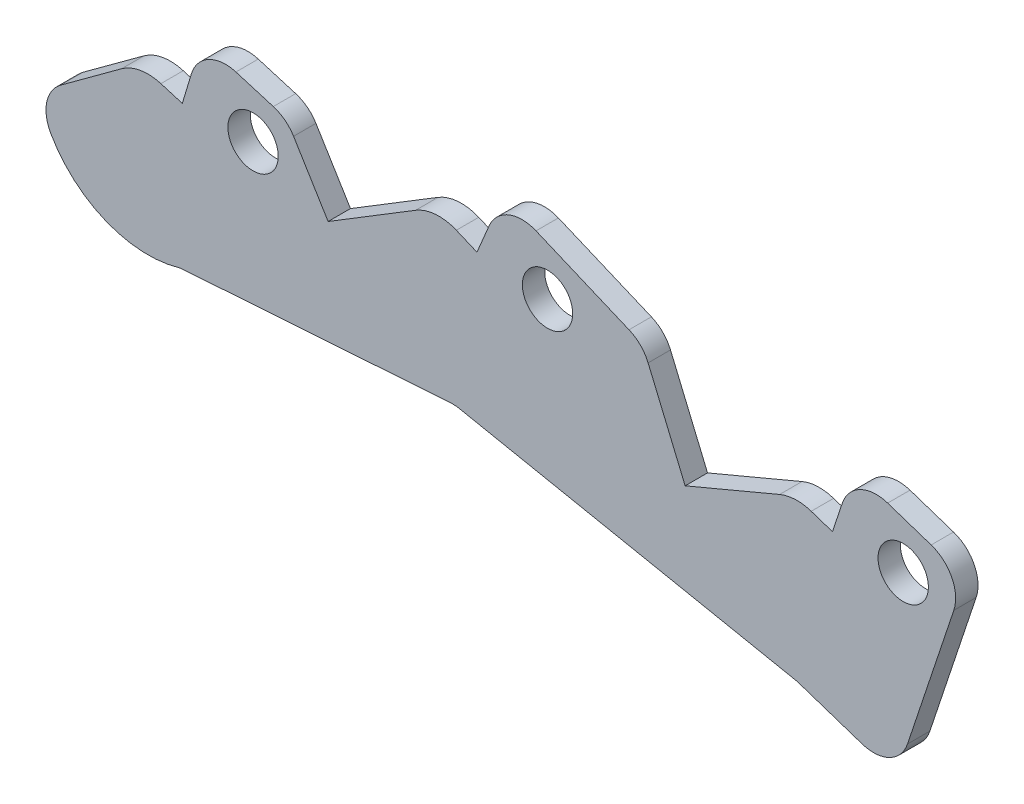
SolidWorks part; units mm, degrees
ref_plane "Front Plane" through (0, 0, 0) normal (0, 0, 1) x (1, 0, 0)
ref_plane "Top Plane" through (0, 0, 0) normal (0, 1, 0) x (1, 0, 0)
ref_plane "Right Plane" through (0, 0, 0) normal (1, 0, 0) x (0, 0, -1)
sketch "Sketch1" plane through (0, 0, 0) normal (0, 0, 1) x (1, 0, 0)
  line L0 (-51.2912, 76.2) -> (64262.6532, 76.2) construction
  line L5 (7.4715, 147.6375) -> (64321.4159, 147.6375) construction
  line L6 (118.3446, 158.75) -> (64432.2889, 158.75) construction
  line L7 (275.7842, 163.5125) -> (64589.7286, 163.5125) construction
  line L8 (55.5625, 439.4786) -> (55.5625, -63874.4658) construction
  line L9 (111.125, 452.7834) -> (111.125, -63861.161) construction
  line L10 (119.0625, 453.8921) -> (119.0625, -63860.0523) construction
  line L11 (99.4961, 73.025) -> (64413.4405, 73.025) construction
  line L12 (93.9525, 3.175) -> (64407.8969, 3.175) construction
  line L13 (33.9504, 0) -> (64347.8947, 0) construction
  line L14 (-39.0951, -3.175) -> (64274.8492, -3.175) construction
  line L15 (-110.0539, -73.025) -> (64203.8905, -73.025) construction
  line L16 (198.1731, 65.0875) -> (64512.1175, 65.0875) construction
  line L17 (201.4993, 77.7875) -> (64515.4437, 77.7875) construction
  line L18 (276.893, 155.575) -> (64590.8373, 155.575) construction
  line L19 (351.1779, 168.275) -> (64665.1223, 168.275) construction
  line L20 (107.95, 410.6516) -> (107.95, -63903.2928) construction
  line L21 (95.25, 453.8921) -> (95.25, -63860.0523) construction
  line L22 (87.3125, 480.5016) -> (87.3125, -63833.4428) construction
  line L23 (34.925, 470.523) -> (34.925, -63843.4213) construction
  line L24 (0, 558.1122) -> (0, -63755.8322) construction
  line L25 (127, 731.8887) -> (127, -63582.0557) construction
  line L26 (133.35, 785.5707) -> (133.35, -63528.3737) construction
  line L27 (146.05, 782.952) -> (146.05, -63530.9923) construction
  line L28 (147.6375, 792.1173) -> (147.6375, -63521.8271) construction
  line L29 (152.4, 819.6129) -> (152.4, -63494.3315) construction
  line L30 (161.925, 852.3458) -> (161.925, -63461.5986) construction
  line L31 (206.375, 822.2315) -> (206.375, -63491.7129) construction
  line L32 (-303.6442, 138.1125) -> (49696.3558, 138.1125) construction
  line L33 (-178.9515, 120.65) -> (49821.0485, 120.65) construction
  point P60 (111.125, -3.175)
  point P61 (119.0625, 0)
  point P62 (133.35, 3.175)
  point P63 (147.6375, 3.175)
  point P64 (107.95, 77.7875)
  point P65 (133.35, 73.025)
  point P66 (152.4, 65.0875)
  point P67 (87.3125, 76.2)
  point P68 (34.925, 147.6375)
  point P69 (55.5625, 163.5125)
  point P70 (111.125, 155.575)
  point P71 (95.25, 163.5125)
  point P72 (127, 138.1125)
  point P73 (146.05, 168.275)
  point P74 (161.925, 158.75)
  point P77 (206.375, 120.65)
  dimension "D1" = 69.85
  dimension "D2" = 73.025
  dimension "D3" = 76.2
  dimension "D4" = 138.1125
  dimension "D5" = 146.05
  dimension "D6" = 150.8125
  dimension "D7" = 149.225
  dimension "D8" = 211.1375
  dimension "D9" = 220.6625
  dimension "D10" = 228.6
  dimension "D11" = 231.775
  dimension "D12" = 236.5375
  dimension "D13" = 241.3
  dimension "D14" = 34.925
  dimension "D15" = 55.5625
  dimension "D16" = 87.3125
  dimension "D17" = 95.25
  dimension "D18" = 107.95
  dimension "D19" = 111.125
  dimension "D20" = 119.0625
  dimension "D21" = 127
  dimension "D22" = 133.35
  dimension "D23" = 146.05
  dimension "D24" = 147.6375
  dimension "D25" = 152.4
  dimension "D26" = 161.925
  dimension "D27" = 206.375
  dimension "D28" = 193.675
sketch "Sketch2" plane through (0, 0, 0) normal (0, 0, 1) x (1, 0, 0)
  line L0 (111.125, -3.175) -> (87.3125, 76.2)
  line L1 (119.0625, 0) -> (107.95, 77.7875)
  line L2 (133.35, 3.175) -> (133.35, 73.025)
  line L3 (147.6375, 3.175) -> (152.4, 65.0875)
  line L4 (152.4, 65.0875) -> (206.375, 120.65)
  line L5 (152.4, 65.0875) -> (127, 138.1125)
  line L6 (133.35, 73.025) -> (161.925, 158.75)
  line L7 (-199881.6554, 158.75) -> (264432.2889, 158.75) construction
  line L8 (133.35, 73.025) -> (95.25, 163.5125)
  line L9 (107.95, 77.7875) -> (146.05, 168.275)
  line L10 (107.95, 77.7875) -> (55.5625, 163.5125)
  line L11 (87.3125, 76.2) -> (111.125, 155.575)
  line L12 (87.3125, 76.2) -> (34.925, 147.6375)
  point P16 (0, 0)
sketch "Sketch4" plane through (0, 0, 0) normal (0, 0, 1) x (1, 0, 0)
  line L0 (87.3125, 76.2) -> (107.95, 77.7875) construction
  line L1 (107.95, 77.7875) -> (133.35, 73.025) construction
  line L2 (133.35, 73.025) -> (152.4, 65.0875) construction
  line L3 (94.8094, 73.5923) -> (100.9401, 74.0639)
  line L4 (114.5151, 73.3262) -> (125.6146, 71.2451)
  line L5 (138.8441, 67.2962) -> (146.05, 64.2937)
  line L6 (111.125, -3.175) -> (87.3125, 76.2) construction
  line L7 (107.1642, 77.6752) -> (108.2868, 69.8175) construction
  line L8 (141.2864, 73.1578) -> (146.9059, 70.8163)
  line L9 (87.069, 79.3656) -> (108.1238, 80.9852) construction
  line L10 (87.556, 73.0344) -> (107.7762, 74.5898) construction
  line L11 (134.2631, 76.0841) -> (153.6212, 68.0183) construction
  line L12 (132.4369, 69.9659) -> (151.1788, 62.1567) construction
  line L13 (146.05, 200782.952) -> (146.05, -263530.9923) construction
  line L14 (108.1238, 80.9852) -> (134.2631, 76.0841) construction
  line L15 (107.7762, 74.5898) -> (132.4369, 69.9659) construction
  line L16 (108.7358, 77.8998) -> (109.8583, 70.042) construction
  line L17 (107.3887, 76.1037) -> (108.9603, 76.3282)
  line L18 (94.3224, 79.9236) -> (100.4531, 80.3952)
  line L19 (115.6854, 79.5674) -> (126.7849, 77.4863)
  line L20 (132.5563, 73.025) -> (132.5563, 65.0875) construction
  line L21 (134.1438, 73.025) -> (134.1438, 65.0875) construction
  line L22 (132.5563, 71.4773) -> (134.1438, 71.4773)
  line L23 (151.4899, 63.6052) -> (151.0029, 57.2739)
  line L24 (153.0727, 63.4835) -> (152.5857, 57.1522)
  line L25 (151.4899, 63.6052) -> (153.0727, 63.4835)
  line L26 (152.4, 65.0875) -> (206.375, 120.65) construction
  line L27 (152.4, 65.0875) -> (127, 138.1125) construction
  line L28 (133.35, 73.025) -> (161.925, 158.75) construction
  line L29 (133.35, 73.025) -> (95.25, 163.5125) construction
  line L30 (87.3125, 76.2) -> (89.5933, 68.5973)
  line L31 (107.95, 77.7875) -> (109.0725, 69.9298)
  line L32 (119.0625, 0) -> (107.95, 77.7875) construction
  line L33 (133.35, 73.025) -> (133.35, 65.0875)
  line L34 (152.4, 65.0875) -> (151.7912, 57.1734)
  line L35 (147.6375, 3.175) -> (152.4, 65.0875) construction
  line L36 (87.0084, 74.4514) -> (88.8216, 68.4073)
  line L37 (107.3887, 76.1037) -> (108.2811, 69.8569)
  line L38 (132.5563, 71.4773) -> (132.5563, 65.1273)
  line L39 (107.95, 77.7875) -> (146.05, 168.275) construction
  line L40 (88.5289, 74.9075) -> (90.3422, 68.8634)
  line L41 (108.9603, 76.3282) -> (109.8527, 70.0814)
  line L42 (134.1438, 71.4773) -> (134.1438, 65.1273)
  line L43 (107.95, 77.7875) -> (55.5625, 163.5125) construction
  line L44 (88.0728, 76.4281) -> (90.3536, 68.8253) construction
  line L45 (86.5522, 75.9719) -> (88.833, 68.3692) construction
  line L46 (87.0084, 74.4514) -> (88.5289, 74.9075)
  line L47 (87.3125, 76.2) -> (111.125, 155.575) construction
  line L48 (87.3125, 76.2) -> (34.925, 147.6375) construction
  line L49 (83.5573, 81.3207) -> (85.4349, 78.7603)
  line L50 (88.2248, 79.2411) -> (89.1372, 82.2822)
  line L51 (106.2944, 80.4967) -> (104.6388, 83.2058)
  line L52 (109.1821, 80.7137) -> (110.4142, 83.6399)
  line L53 (132.1179, 75.9512) -> (130.8858, 78.8774)
  line L54 (134.354, 76.0371) -> (135.358, 79.0491)
  line L55 (151.3569, 68.0863) -> (150.3139, 71.0851)
  line L56 (154.6123, 67.3649) -> (156.8246, 69.6422)
  line L57 (82.2772, 80.3819) -> (84.1548, 77.8215)
  line L58 (89.7454, 78.7849) -> (90.6577, 81.826)
  line L59 (110.6452, 80.0977) -> (111.8773, 83.0238)
  line L60 (135.8601, 75.5351) -> (136.8641, 78.5471)
  line L61 (155.751, 66.2587) -> (157.9633, 68.5361)
  line L62 (149.8576, 67.5648) -> (148.8145, 70.5635)
  line L63 (130.6548, 75.3352) -> (129.4227, 78.2613)
  line L64 (104.9398, 79.6689) -> (103.2842, 82.378)
  line L65 (83.5573, 81.3207) -> (82.2772, 80.3819)
  line L66 (156.8246, 69.6422) -> (157.9633, 68.5361)
  line L67 (84.1548, 77.8215) -> (85.4349, 78.7603)
  line L68 (88.2248, 79.2411) -> (89.7454, 78.7849)
  line L69 (154.6123, 67.3649) -> (155.751, 66.2587)
  line L70 (149.8576, 67.5648) -> (151.3569, 68.0863)
  line L71 (148.8145, 70.5635) -> (150.3139, 71.0851)
  line L72 (129.4227, 78.2613) -> (130.8858, 78.8774)
  line L73 (130.6548, 75.3352) -> (132.1179, 75.9512)
  line L74 (135.358, 79.0491) -> (136.8641, 78.5471)
  line L75 (134.354, 76.0371) -> (135.8601, 75.5351)
  line L76 (89.1372, 82.2822) -> (90.6577, 81.826)
  line L77 (103.2842, 82.378) -> (104.6388, 83.2058)
  line L78 (104.9398, 79.6689) -> (106.2944, 80.4967)
  line L79 (110.4142, 83.6399) -> (111.8773, 83.0238)
  line L80 (109.1821, 80.7137) -> (110.6452, 80.0977)
  circle A0 centre (87.3125, 76.2) radius 7.9375
  circle A1 centre (107.95, 77.7875) radius 7.9375
  circle A2 centre (133.35, 73.025) radius 7.9375
  circle A3 centre (152.4, 65.0875) radius 7.9375
  circle A16 centre (152.4, 65.0875) radius 4.7625 construction
  circle A17 centre (133.35, 73.025) radius 4.7625 construction
  circle A18 centre (107.95, 77.7875) radius 4.7625 construction
  circle A19 centre (87.3125, 76.2) radius 4.7625 construction
  circle A20 centre (155.7184, 68.5035) radius 1.5875
  circle A21 centre (150.8354, 69.5857) radius 1.5875
  circle A22 centre (134.856, 77.5431) radius 1.5875
  circle A23 centre (131.5019, 77.4143) radius 1.5875
  circle A24 centre (109.7981, 82.1768) radius 1.5875
  circle A25 centre (105.4666, 81.8513) radius 1.5875
  circle A26 centre (88.681, 80.7616) radius 1.5875
  circle A27 centre (84.4961, 80.0405) radius 1.5875
  arc A28 (154.6123, 67.3649) -> (151.3569, 68.0863) centre (152.4, 65.0875) ccw
  arc A29 (156.8246, 69.6422) -> (150.3139, 71.0851) centre (152.4, 65.0875) ccw
  arc A30 (134.354, 76.0371) -> (132.1179, 75.9512) centre (133.35, 73.025) ccw
  arc A31 (130.8858, 78.8774) -> (135.358, 79.0491) centre (133.35, 73.025) cw
  arc A32 (109.1821, 80.7137) -> (106.2944, 80.4967) centre (107.95, 77.7875) ccw
  arc A33 (110.4142, 83.6399) -> (104.6388, 83.2058) centre (107.95, 77.7875) ccw
  arc A34 (88.2248, 79.2411) -> (85.4349, 78.7603) centre (87.3125, 76.2) ccw
  arc A35 (89.1372, 82.2822) -> (83.5573, 81.3207) centre (87.3125, 76.2) ccw
  dimension "D1" = 15.875
  dimension "D15" = 9.525
  dimension "D16" = 3.175
  dimension "D17" = 1.5875
  dimension "D2" = 3.175
  dimension "D4" = 3.175
  dimension "D5" = 3.175
  dimension "D7" = 0.7937
  dimension "D9" = 6.35
  dimension "D10" = 6.35
  dimension "D11" = 6.35
  dimension "D12" = 0.7937
  dimension "D14" = 6.35
  dimension "D13" = 0.7937
  dimension "D3" = 3.175
  dimension "D8" = 0.7937
  dimension "D18" = 1.5875
sketch "Sketch5" plane through (0, 0, 0) normal (0, 0, 1) x (1, 0, 0)
  line L0 (87.3125, 76.2) -> (86.3737, 77.4802) construction
  line L1 (86.3737, 77.4802) -> (85.4349, 78.7603) construction
  line L2 (85.4349, 78.7603) -> (83.5573, 81.3207) construction
  line L3 (83.5573, 81.3207) -> (78.4367, 77.5655) construction
  line L4 (78.4367, 77.5655) -> (80.3142, 75.0052) construction
  line L5 (80.3142, 75.0052) -> (85.4349, 78.7603) construction
  line L6 (82.2772, 80.3819) -> (84.1548, 77.8215) construction
  line L7 (79.7168, 78.5043) -> (81.5944, 75.944) construction
  line L8 (87.3125, 76.2) -> (34.925, 147.6375) construction
  line L9 (83.5573, 81.3207) -> (82.6186, 82.6008) construction
  line L10 (87.3125, 76.2) -> (87.7687, 77.7205) construction
  line L11 (87.7687, 77.7205) -> (88.2248, 79.2411) construction
  line L12 (88.2248, 79.2411) -> (89.1372, 82.2822) construction
  line L13 (89.1372, 82.2822) -> (83.055, 84.1069) construction
  line L14 (83.055, 84.1069) -> (82.1426, 81.0658) construction
  line L15 (82.1426, 81.0658) -> (88.2248, 79.2411) construction
  line L16 (87.6166, 82.7384) -> (86.7043, 79.6973) construction
  line L17 (84.5755, 83.6507) -> (83.6632, 80.6096) construction
  line L18 (89.1372, 82.2822) -> (89.5933, 83.8027) construction
  line L19 (87.3125, 76.2) -> (111.125, 155.575) construction
  line L20 (88.2248, 79.2411) -> (89.5933, 83.8027)
  line L21 (85.4349, 78.7603) -> (79.5685, 74.4583)
  line L22 (109.1821, 80.7137) -> (111.0302, 85.103)
  line L23 (107.95, 77.7875) -> (146.05, 168.275) construction
  line L24 (134.354, 76.0371) -> (135.8601, 80.5552)
  line L25 (133.35, 73.025) -> (161.925, 158.75) construction
  line L26 (106.2944, 80.4967) -> (100.0869, 76.7032)
  line L27 (107.95, 77.7875) -> (55.5625, 163.5125) construction
  line L28 (132.1179, 75.9512) -> (125.4132, 73.1281)
  line L29 (133.35, 73.025) -> (95.25, 163.5125) construction
  line L30 (125.4132, 73.1281) -> (122.384, 80.3224)
  line L31 (100.0869, 76.7032) -> (97.13, 81.5417)
  line L32 (116.8826, 82.6388) -> (111.0302, 85.103)
  line L33 (89.5933, 83.8027) -> (97.13, 81.5417)
  line L34 (111.0302, 85.103) -> (122.384, 80.3224)
  line L35 (133.35, 73.025) -> (107.95, 77.7875) construction
  line L36 (107.95, 77.7875) -> (87.3125, 76.2) construction
  line L37 (133.35, 65.0875) -> (109.0725, 69.9298)
  line L38 (119.0625, 0) -> (107.95, 77.7875) construction
  line L39 (109.0725, 69.9298) -> (89.5933, 68.5973)
  line L40 (111.125, -3.175) -> (87.3125, 76.2) construction
  line L41 (97.6313, 76.9937) -> (99.3329, 69.2635) construction
  line L42 (120.65, 75.4063) -> (121.2113, 67.5086) construction
  line L43 (95.6755, 81.9781) -> (94.7632, 78.937) construction
  line L44 (116.8826, 82.6388) -> (115.6505, 79.7126) construction
  line L45 (95.6755, 81.9781) -> (89.5933, 83.8027)
  line L46 (141.8842, 78.5471) -> (140.8802, 75.5351) construction
  line L47 (140.8802, 75.5351) -> (136.9929, 63.8732) construction
  line L48 (133.35, 65.0875) -> (140.3815, 62.7437)
  line L49 (141.8842, 78.5471) -> (145.2728, 77.4176)
  line L50 (145.2728, 77.4176) -> (140.3815, 62.7437)
  line L51 (135.8601, 80.5552) -> (141.8842, 78.5471)
  line L52 (88.2248, 79.2411) -> (89.7454, 78.7849)
  line L53 (89.7454, 78.7849) -> (91.1139, 83.3466)
  line L54 (109.1821, 80.7137) -> (110.6452, 80.0977)
  line L55 (110.6452, 80.0977) -> (112.4933, 84.4869)
  line L56 (134.354, 76.0371) -> (135.8601, 75.5351)
  line L57 (135.8601, 75.5351) -> (137.3661, 80.0532)
  circle A0 centre (87.3125, 76.2) radius 7.9375
  circle A1 centre (107.95, 77.7875) radius 7.9375
  circle A2 centre (133.35, 73.025) radius 7.9375
  circle A3 centre (87.3125, 76.2) radius 3.175
  circle A4 centre (107.95, 77.7875) radius 3.175
  circle A5 centre (133.35, 73.025) radius 3.175
  circle A7 centre (98.4821, 73.1286) radius 1.7859 construction
  circle A8 centre (120.9306, 71.4574) radius 1.7859 construction
  circle A9 centre (94.7632, 78.937) radius 1.7859
  circle A10 centre (115.6505, 79.7126) radius 1.7859
  circle A11 centre (140.8802, 75.5351) radius 1.7859
  circle A12 centre (152.4, 65.0875) radius 3.175 construction
  circle A13 centre (152.4, 65.0875) radius 7.9375 construction
  dimension "D1" = 15.875
  dimension "D4" = 6.35
  dimension "D14" = 6.35
  dimension "D15" = 3.5719
  dimension "D16" = 3.175
  dimension "D17" = 3.5719
  dimension "D2" = 1.5875
  dimension "D3" = 1.5875
  dimension "D5" = 1.5875
  dimension "D6" = 1.5875
  dimension "D7" = 3.175
  dimension "D8" = 1.5875
  dimension "D9" = 1.5875
  dimension "D10" = 1.5875
  dimension "D11" = 1.5875
  dimension "D12" = 6.35
  dimension "D13" = 3.175
  dimension "D18" = 1.5875
extrude "Boss-Extrude1" add sketch "Sketch5" along normal blind 1.5875 contours A11 A2 L48 L50 L49 L51 | A11 A2 L24 A5 L28 L37 | A5 | A10 A1 L37 A2 L30 L34 L32 | A10 A1 L22 A4 L26 L39 | A9 A0 L39 A1 L31 L33 | A4 | A9 A0 L20 A3 L21 | A3 L28
fillet "Fillet1" radius 2.54 10 edges at (122.384, 80.3224, 0.7937) (97.13, 81.5417, 0.7937) (79.5685, 74.4583, 0.7937) (133.35, 65.0875, 0.7937) (109.0725, 69.9298, 0.7937) (140.3815, 62.7437, 0.7937) (145.2728, 77.4176, 0.7937) (137.3661, 80.0532, 0.7937) (112.4933, 84.4869, 0.7937) (91.1139, 83.3466, 0.7937)
